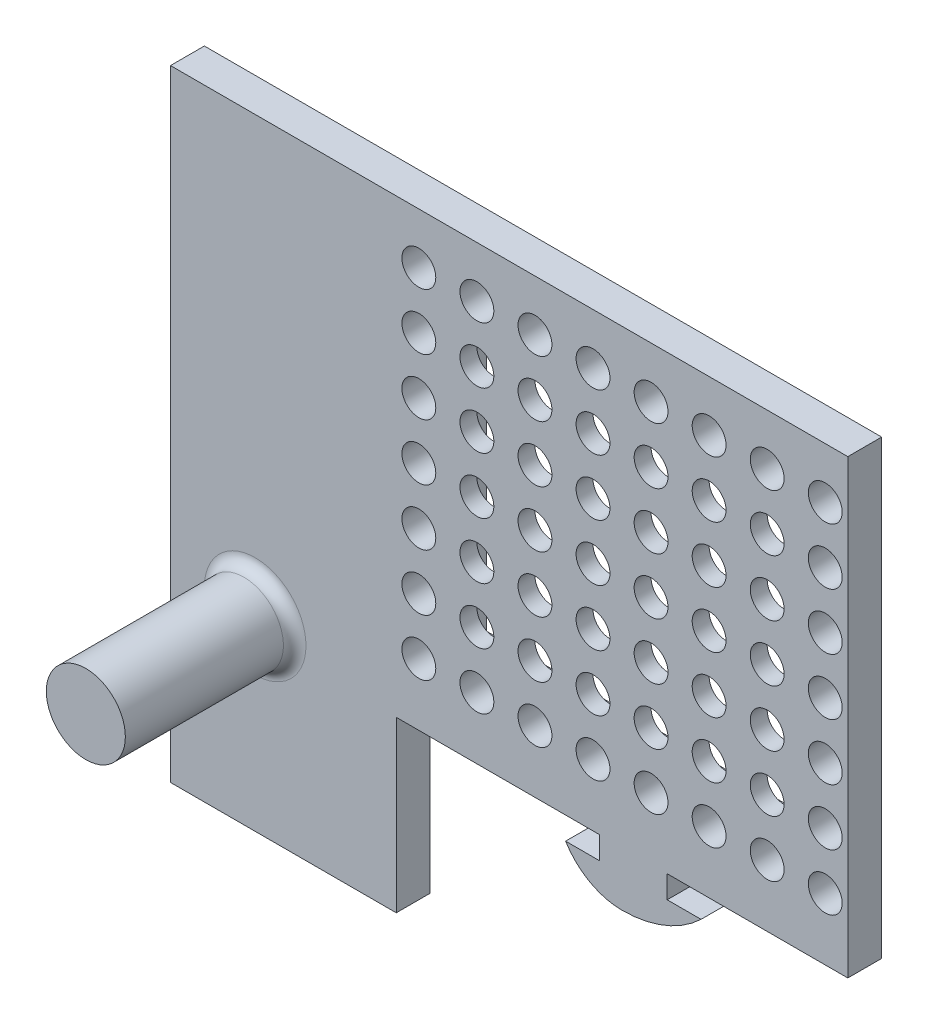
SolidWorks part; units mm, degrees
ref_plane "Plan de face" through (0, 0, 0) normal (0, 0, 1) x (1, 0, 0)
ref_plane "Plan de dessus" through (0, 0, 0) normal (0, 1, 0) x (1, 0, 0)
ref_plane "Plan de droite" through (0, 0, 0) normal (1, 0, 0) x (0, 0, -1)
sketch "Esquisse1" plane through (0, 0, 0) normal (0, 0, 1) x (1, 0, 0)
  line L0 (-18, 2) -> (0, 2)
  line L2 (22, 2) -> (22, 42)
  line L3 (22, 42) -> (-18, 42)
  line L5 (22, 2) -> (-18, 42) construction
  line L6 (22, 42) -> (-18, 2) construction
  line L7 (22, 2) -> (6, 2)
  line L8 (6, 2) -> (6, 0)
  line L9 (0, 2) -> (0, 0)
  line L10 (0, 0) -> (-3, 0)
  line L11 (6, 0) -> (9, 0)
  line L12 (-18, 42) -> (-38, 42)
  line L13 (-38, 42) -> (-38, -13)
  line L14 (-38, -13) -> (-18, -13)
  line L15 (-18, -13) -> (-18, 2)
  arc A2 (9, 0) -> (2, -2.8036) centre (2, 7.3369) cw
  arc A3 (2, -2.8036) -> (-3, 0) centre (2, 3.0567) cw
  point P10 (2, 22)
  dimension "D9" = 20
  dimension "D10" = 55
  dimension "D1" = 40
  dimension "D2" = 40
  dimension "D3" = 2
  dimension "D4" = 2
  dimension "D5" = 3
  dimension "D6" = 3
  dimension "D7" = 18
  dimension "D8" = 16
  dimension "D11" = 20
extrude "Boss.-Extru.1" add sketch "Esquisse1" along normal blind 3
sketch "Esquisse2" plane through (0, 0, 3) normal (0, 0, 1) x (1, 0, 0)
  line L1 (22, 2) -> (22, 42) construction
  circle A0 centre (-16, 37.4899) radius 1.5
  circle A1 centre (-10.8571, 37.4899) radius 1.5
  circle A2 centre (-5.7143, 37.4899) radius 1.5
  circle A3 centre (-0.5714, 37.4899) radius 1.5
  circle A4 centre (4.5714, 37.4899) radius 1.5
  circle A5 centre (9.7143, 37.4899) radius 1.5
  circle A6 centre (14.8571, 37.4899) radius 1.5
  circle A7 centre (20, 37.4899) radius 1.5
  circle A8 centre (-10.8571, 32.4899) radius 1.5
  circle A9 centre (-5.7143, 32.4899) radius 1.5
  circle A10 centre (-0.5714, 32.4899) radius 1.5
  circle A11 centre (4.5714, 32.4899) radius 1.5
  circle A12 centre (9.7143, 32.4899) radius 1.5
  circle A13 centre (14.8571, 32.4899) radius 1.5
  circle A14 centre (-10.8571, 27.4899) radius 1.5
  circle A15 centre (-5.7143, 27.4899) radius 1.5
  circle A16 centre (-0.5714, 27.4899) radius 1.5
  circle A17 centre (4.5714, 27.4899) radius 1.5
  circle A18 centre (9.7143, 27.4899) radius 1.5
  circle A19 centre (14.8571, 27.4899) radius 1.5
  circle A20 centre (-10.8571, 22.4899) radius 1.5
  circle A21 centre (-5.7143, 22.4899) radius 1.5
  circle A22 centre (-0.5714, 22.4899) radius 1.5
  circle A23 centre (4.5714, 22.4899) radius 1.5
  circle A24 centre (9.7143, 22.4899) radius 1.5
  circle A25 centre (14.8571, 22.4899) radius 1.5
  circle A26 centre (-10.8571, 17.4899) radius 1.5
  circle A27 centre (-5.7143, 17.4899) radius 1.5
  circle A28 centre (-0.5714, 17.4899) radius 1.5
  circle A29 centre (4.5714, 17.4899) radius 1.5
  circle A30 centre (9.7143, 17.4899) radius 1.5
  circle A31 centre (14.8571, 17.4899) radius 1.5
  circle A32 centre (-10.8571, 12.4899) radius 1.5
  circle A33 centre (-5.7143, 12.4899) radius 1.5
  circle A34 centre (-0.5714, 12.4899) radius 1.5
  circle A35 centre (4.5714, 12.4899) radius 1.5
  circle A36 centre (9.7143, 12.4899) radius 1.5
  circle A37 centre (14.8571, 12.4899) radius 1.5
  circle A38 centre (-10.8571, 7.4899) radius 1.5
  circle A39 centre (-5.7143, 7.4899) radius 1.5
  circle A40 centre (-0.5714, 7.4899) radius 1.5
  circle A41 centre (4.5714, 7.4899) radius 1.5
  circle A42 centre (9.7143, 7.4899) radius 1.5
  circle A43 centre (14.8571, 7.4899) radius 1.5
  circle A44 centre (-16, 32.4899) radius 1.5
  circle A45 centre (-16, 27.4899) radius 1.5
  circle A46 centre (-16, 22.4899) radius 1.5
  circle A47 centre (-16, 17.4899) radius 1.5
  circle A48 centre (-16, 12.4899) radius 1.5
  circle A49 centre (-16, 7.4899) radius 1.5
  circle A50 centre (20, 32.4899) radius 1.5
  circle A51 centre (20, 27.4899) radius 1.5
  circle A52 centre (20, 22.4899) radius 1.5
  circle A53 centre (20, 17.4899) radius 1.5
  circle A54 centre (20, 12.4899) radius 1.5
  circle A55 centre (20, 7.4899) radius 1.5
  dimension "D1" = 8
  dimension "D2" = 3
  dimension "D4" = 2
  dimension "D5" = 7
  dimension "D6" = 7
  dimension "D7" = 7
extrude "Enlèv. mat.-Extru.1" cut sketch "Esquisse2" against normal through all
sketch "Esquisse3" plane through (0, 0, 3) normal (0, 0, 1) x (1, 0, 0)
  line L0 (-38, -13) -> (-18, -13) construction
  line L1 (-18, -13) -> (-18, 2) construction
  circle A0 centre (-30.5, 3.5) radius 3.5
  dimension "D1" = 16.5
  dimension "D2" = 7
  dimension "D3" = 12.5
extrude "Boss.-Extru.2" add sketch "Esquisse3" along normal blind 15
fillet "Congé1" radius 1 1 edges at (-34, 3.5, 3)
sketch "Esquisse4" plane through (0, 0, 0) normal (0, 0, 1) x (1, 0, 0)
  line L0 (22, 42) -> (-38, 42) construction
  line L1 (17, 9.6016) -> (-13, 9.6016)
  line L2 (17, 9.6016) -> (17, 34.3984)
  line L3 (17, 34.3984) -> (-13, 34.3984)
  line L4 (-13, 9.6016) -> (-13, 34.3984)
  line L5 (17, 9.6016) -> (-13, 34.3984) construction
  line L6 (17, 34.3984) -> (-13, 9.6016) construction
  line L8 (22, 2) -> (22, 42) construction
  point P0 (2, 22)
  dimension "D1" = 20
  dimension "D2" = 5
  dimension "D3" = 5
extrude "Enlèv. mat.-Extru.3" cut sketch "Esquisse4" along normal blind 1.5
